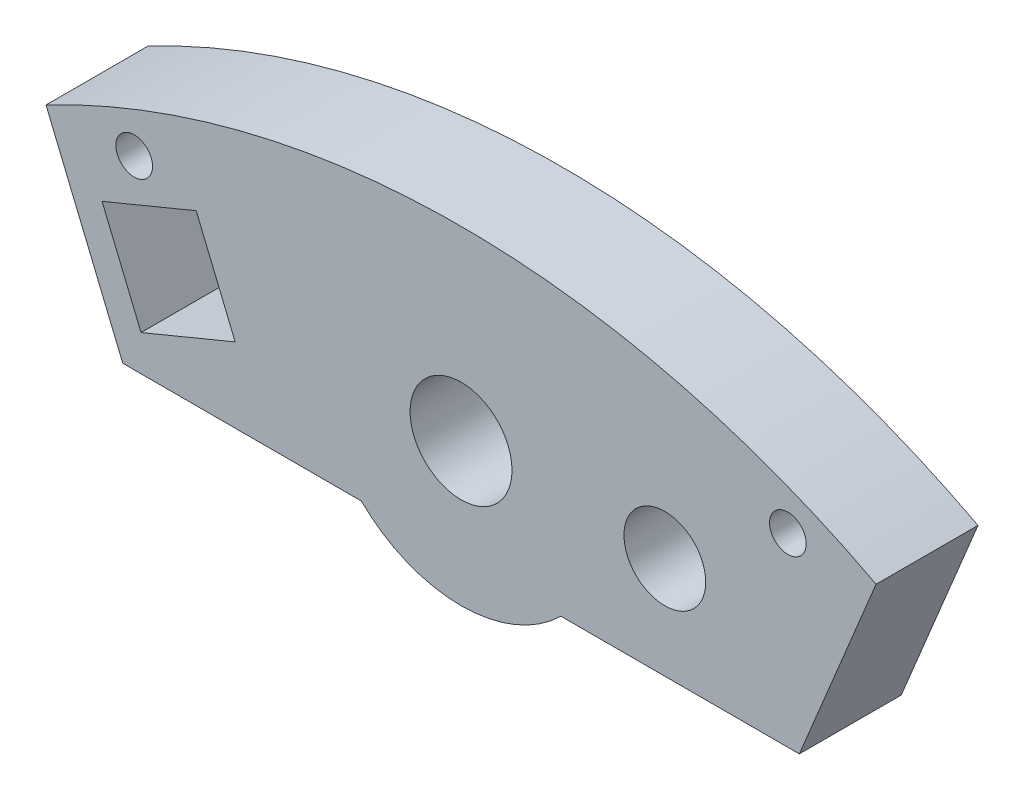
SolidWorks part; units mm, degrees
ref_plane "Front Plane" through (0, 0, 0) normal (0, 0, 1) x (1, 0, 0)
ref_plane "Top Plane" through (0, 0, 0) normal (0, 1, 0) x (1, 0, 0)
ref_plane "Right Plane" through (0, 0, 0) normal (1, 0, 0) x (0, 0, -1)
sketch "Sketch1" plane through (0, 0, 0) normal (0, 0, 1) x (1, 0, 0)
  line L0 (-46.9014, 0) -> (43.5211, 0) construction
  line L1 (0, 38.5211) -> (0, -80.4339) construction
  line L2 (-33.5349, -69.25) -> (36.7559, -69.25) construction
  line L3 (0, -69.25) -> (-37.9703, 22.4183) construction
  line L4 (-40.7356, 8.1894) -> (-33.2013, -10)
  line L5 (-25.9953, 6.5738) -> (-35.2341, 2.7469)
  line L6 (-35.2341, 2.7469) -> (-31.4072, -6.4918)
  line L7 (-31.4072, -6.4918) -> (-22.1684, -2.665)
  line L8 (-22.1684, -2.665) -> (-25.9953, 6.5738)
  line L9 (-33.2013, -10) -> (-9.798, -10)
  line L10 (33.2013, -10) -> (9.798, -10)
  line L11 (40.7356, 8.1894) -> (33.2013, -10)
  circle A0 centre (20, 0) radius 4.0125
  circle A1 centre (-28.7013, 0.041) radius 5 construction
  arc A2 (40.7356, 8.1894) -> (-40.7356, 8.1894) centre (0, -69.25) ccw
  arc A5 (-9.798, -10) -> (9.798, -10) centre (0, 0) ccw
  circle A6 centre (0, 0) radius 5
  circle A7 centre (-32.0765, 8.1894) radius 1.8
  circle A8 centre (32.0765, 8.1894) radius 1.8
  dimension "D1" = 20
  dimension "D2" = 8.025
  dimension "D7" = 75
  dimension "D8" = 175
  dimension "D9" = 3
  dimension "D10" = 14
  dimension "D12" = 10
  dimension "D13" = 3.6
  dimension "D14" = 32.0765
  dimension "D3" = 69.25
  dimension "D4" = 22.5
  dimension "D5" = 10
  dimension "D6" = 90
  dimension "D11" = 10
extrude "Boss-Extrude1" add sketch "Sketch1" along normal blind 10
